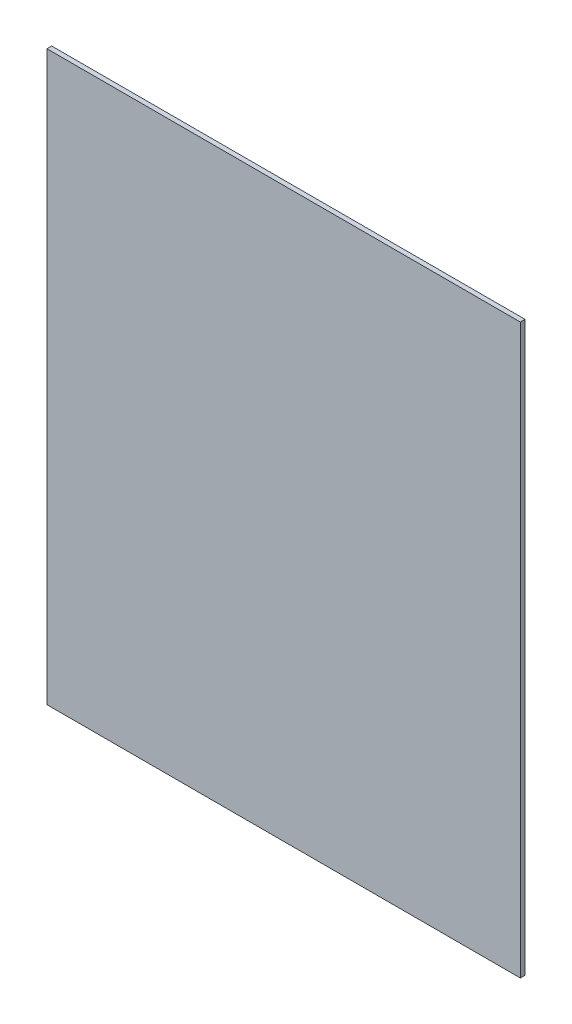
SolidWorks part; units mm, degrees
ref_plane "Front Plane" through (0, 0, 0) normal (0, 0, 1) x (1, 0, 0)
ref_plane "Top Plane" through (0, 0, 0) normal (0, 1, 0) x (1, 0, 0)
ref_plane "Right Plane" through (0, 0, 0) normal (1, 0, 0) x (0, 0, -1)
sketch "Sketch2" plane through (0, 0, 0) normal (0, 0, 1) x (1, 0, 0)
  line L1 (50, -60) -> (-50, -60)
  line L2 (50, -60) -> (50, 60)
  line L3 (50, 60) -> (-50, 60)
  line L4 (-50, -60) -> (-50, 60)
  line L5 (50, -60) -> (-50, 60) construction
  line L6 (50, 60) -> (-50, -60) construction
  point P0 (0, 0)
  dimension "D1" = 100
  dimension "D2" = 120
extrude "Boss-Extrude1" add sketch "Sketch2" along normal blind 1
